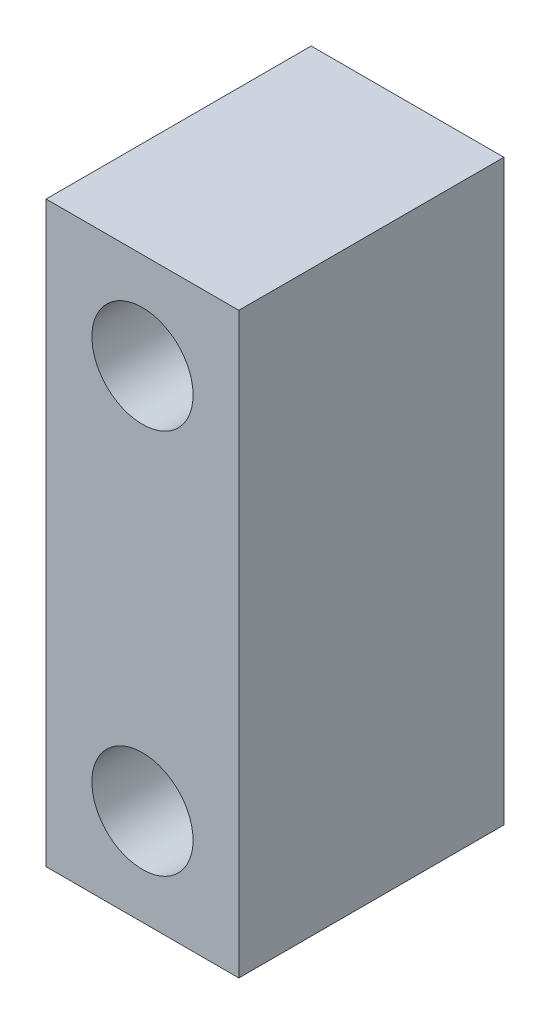
SolidWorks part; units mm, degrees
material "ﾁｰｸ材"
ref_plane "正面" through (0, 0, 0) normal (0, 0, 1) x (1, 0, 0)
ref_plane "平面" through (0, 0, 0) normal (0, 1, 0) x (1, 0, 0)
ref_plane "右側面" through (0, 0, 0) normal (1, 0, 0) x (0, 0, -1)
sketch "ｽｹｯﾁ1" plane through (0, 0, 0) normal (0, 0, 1) x (1, 0, 0)
  line L1 (2, 6) -> (-2, 6)
  line L2 (2, 6) -> (2, -6)
  line L3 (2, -6) -> (-2, -6)
  line L4 (-2, 6) -> (-2, -6)
  line L5 (2, 6) -> (-2, -6) construction
  line L6 (2, -6) -> (-2, 6) construction
  point P0 (0, 0)
  dimension "D1" = 12
  dimension "D2" = 4
extrude "ﾎﾞｽ - 押し出し1" add sketch "ｽｹｯﾁ1" along normal blind 5.5
sketch "ｽｹｯﾁ2" plane through (0, 0, 5.5) normal (0, 0, 1) x (1, 0, 0)
  circle A0 centre (0, 4) radius 1.05
  circle A1 centre (0, -4) radius 1.05
  point P4 (0, 0)
  dimension "D1" = 2.1
  dimension "D2" = 4
  dimension "D3" = 4
extrude "ｶｯﾄ - 押し出し1" cut sketch "ｽｹｯﾁ2" against normal through all
